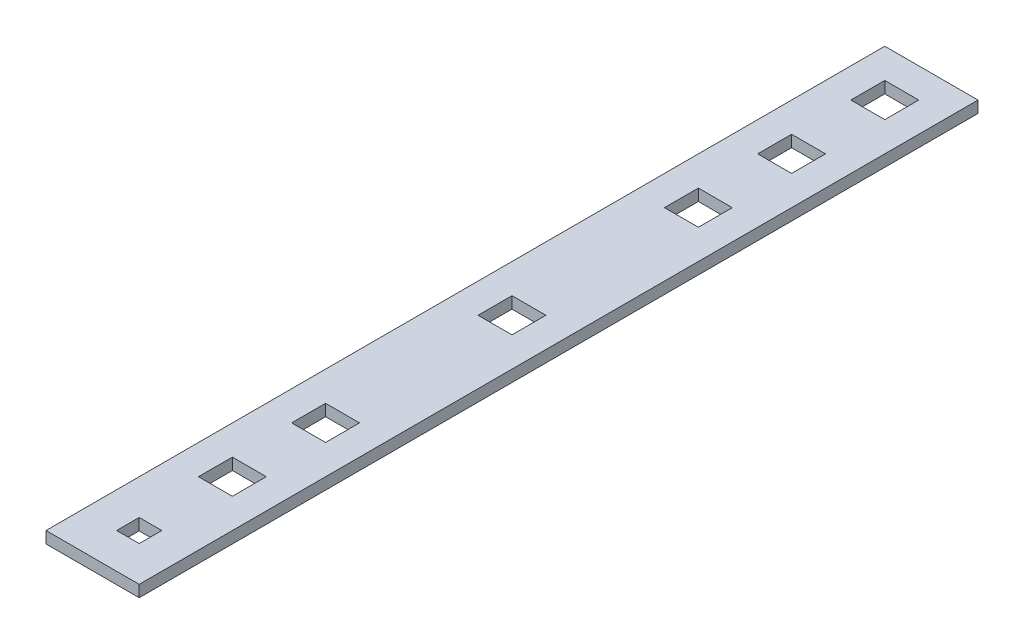
SolidWorks part; units mm, degrees
ref_plane "Front Plane" through (0, 0, 0) normal (0, 0, 1) x (1, 0, 0)
ref_plane "Top Plane" through (0, 0, 0) normal (0, 1, 0) x (1, 0, 0)
ref_plane "Right Plane" through (0, 0, 0) normal (1, 0, 0) x (0, 0, -1)
sketch "Sketch1" plane through (0, 0, 0) normal (0, 1, 0) x (1, 0, 0)
  line L0 (4.0372, 84.7975) -> (4.0372, 80.1747)
  line L1 (0, 101.5375) -> (12.7, 101.5375)
  line L2 (0, 101.5375) -> (0, -12.7625)
  line L3 (0, -12.7625) -> (12.7, -12.7625)
  line L4 (12.7, 101.5375) -> (12.7, -12.7625)
  line L5 (4.0372, 97.4975) -> (8.66, 97.4975)
  line L6 (4.0372, 97.4975) -> (4.0372, 92.8747)
  line L7 (4.0372, 92.8747) -> (8.66, 92.8747)
  line L8 (8.66, 97.4975) -> (8.66, 92.8747)
  line L9 (4.0372, 84.7975) -> (8.66, 84.7975)
  line L10 (8.66, 84.7975) -> (8.66, 80.1747)
  line L11 (4.0372, 80.1747) -> (8.66, 80.1747)
  line L12 (4.0372, 72.0975) -> (4.0372, 67.4747)
  line L13 (4.0372, 72.0975) -> (8.66, 72.0975)
  line L14 (8.66, 72.0975) -> (8.66, 67.4747)
  line L15 (4.0372, 67.4747) -> (8.66, 67.4747)
  line L20 (4.0372, 46.6975) -> (4.0372, 42.0747)
  line L21 (4.0372, 46.6975) -> (8.66, 46.6975)
  line L22 (8.66, 46.6975) -> (8.66, 42.0747)
  line L23 (4.0372, 42.0747) -> (8.66, 42.0747)
  line L28 (4.0372, 21.2975) -> (4.0372, 16.6747)
  line L29 (4.0372, 21.2975) -> (8.66, 21.2975)
  line L30 (8.66, 21.2975) -> (8.66, 16.6747)
  line L31 (4.0372, 16.6747) -> (8.66, 16.6747)
  line L32 (4.0372, 8.5975) -> (4.0372, 3.9747)
  line L33 (4.0372, 8.5975) -> (8.66, 8.5975)
  line L34 (8.66, 8.5975) -> (8.66, 3.9747)
  line L35 (4.0372, 3.9747) -> (8.66, 3.9747)
  line L40 (4.0372, 33.9975) -> (4.0372, 29.3747) [skipped]
  line L41 (4.0372, 29.3747) -> (8.66, 29.3747) [skipped]
  line L42 (8.66, 33.9975) -> (8.66, 29.3747) [skipped]
  line L43 (4.0372, 33.9975) -> (8.66, 33.9975) [skipped]
  line L44 (4.0372, 59.3975) -> (4.0372, 54.7747) [skipped]
  line L45 (4.0372, 54.7747) -> (8.66, 54.7747) [skipped]
  line L46 (8.66, 59.3975) -> (8.66, 54.7747) [skipped]
  line L47 (4.0372, 59.3975) -> (8.66, 59.3975) [skipped]
  line L49 (4.81, -4.8725) -> (7.89, -4.8725)
  line L50 (4.81, -4.8725) -> (4.81, -7.9525)
  line L51 (4.81, -7.9525) -> (7.89, -7.9525)
  line L52 (7.89, -4.8725) -> (7.89, -7.9525)
  line L53 (8.66, -4.1025) -> (8.66, -8.7253) [skipped]
  line L54 (4.0372, -8.7253) -> (8.66, -8.7253) [skipped]
  line L55 (4.0372, -4.1025) -> (4.0372, -8.7253) [skipped]
  line L56 (4.0372, -4.1025) -> (8.66, -4.1025) [skipped]
  point P8 (6.35, 101.5375)
  dimension "D1" = 12.7
  dimension "D2" = 114.3
  dimension "D3" = 4.6228
  dimension "D4" = 4.6228
  dimension "D5" = 4.04
  dimension "D6" = 4.04
  dimension "D8" = 3.08
  dimension "D9" = 3.08
  dimension "D10" = 4.81
  dimension "D11" = 4.81
  dimension "D7" = 9
extrude "Boss-Extrude1" add sketch "Sketch1" along normal blind 1.5875
